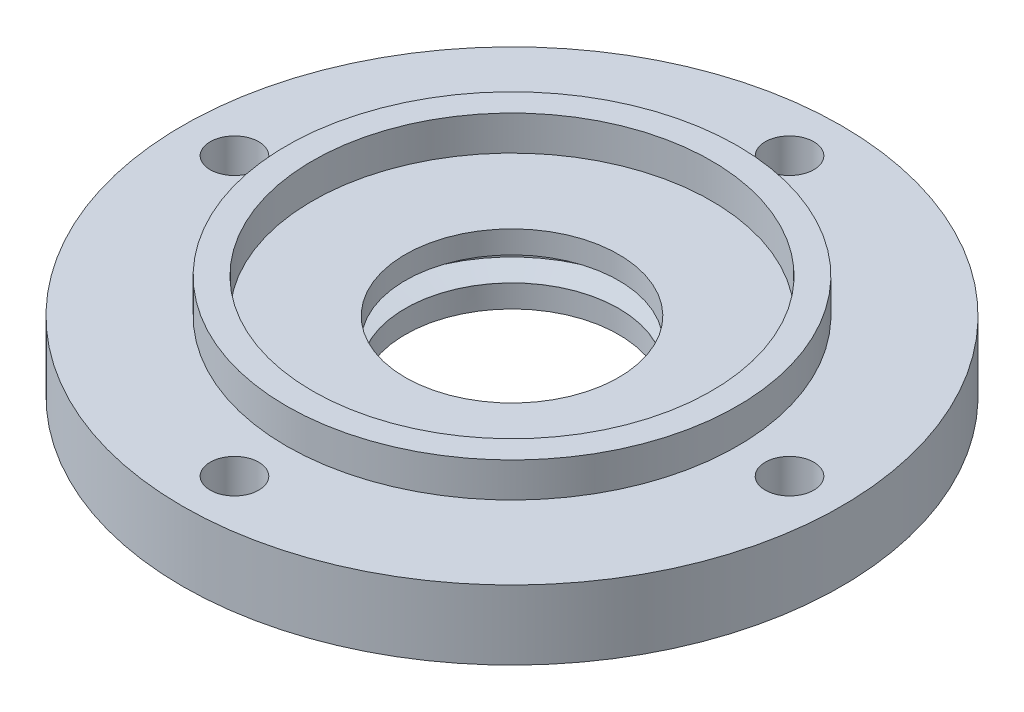
SolidWorks part; units mm, degrees
ref_plane "Front Plane" through (0, 0, 0) normal (0, 0, 1) x (1, 0, 0)
ref_plane "Top Plane" through (0, 0, 0) normal (0, 1, 0) x (1, 0, 0)
ref_plane "Right Plane" through (0, 0, 0) normal (1, 0, 0) x (0, 0, -1)
sketch "Sketch1" plane through (0, 0, 0) normal (0, 1, 0) x (1, 0, 0)
  circle A0 centre (0, 0) radius 95
  dimension "D1" = 190
extrude "Boss-Extrude1" add sketch "Sketch1" along normal mid plane 20 contours A0
sketch "Sketch2" plane through (0, 10, 0) normal (0, 1, 0) x (1, 0, 0)
  circle A0 centre (0, 0) radius 65
  dimension "D1" = 130
extrude "Boss-Extrude2" add sketch "Sketch2" along normal blind 10
sketch "Sketch3" plane through (0, 20, 0) normal (0, 1, 0) x (1, 0, 0)
  circle A0 centre (0, 0) radius 57.5
  dimension "D1" = 115
extrude "Cut-Extrude1" cut sketch "Sketch3" against normal blind 10
sketch "Sketch4" plane through (0, 10, 0) normal (0, 1, 0) x (1, 0, 0)
  line L0 (0, -105.345) -> (0, 103.136) construction
  circle A0 centre (0, 80) radius 7
  circle A1 centre (80, 0) radius 7
  circle A2 centre (0, -80) radius 7
  circle A3 centre (-80, 0) radius 7
  point P15 (0, 0)
  dimension "D2" = 14
  dimension "D1" = 80
  dimension "D3" = 4
extrude "Cut-Extrude2" cut sketch "Sketch4" against normal through all
sketch "Sketch5" plane through (0, 10, 0) normal (0, 1, 0) x (1, 0, 0)
  circle A0 centre (0, 0) radius 30.75
  dimension "D1" = 61.5
extrude "Cut-Extrude3" cut sketch "Sketch5" against normal through all
sketch "Sketch6" plane through (0, 0, 0) normal (1, 0, 0) x (0, 0, -1)
  line L0 (0, -20.8168) -> (0, 0) construction
  line L13 (0, 3.5) -> (-30.8148, 3.5)
  line L14 (-38.5, -2.5) -> (-38.5, 2.5)
  line L15 (-30.8148, 3.5) -> (-38.5, 2.5)
  line L18 (0, 3.5) -> (0, -3.5)
  line L19 (0, -3.5) -> (-30.8148, -3.5)
  line L21 (-30.8148, -3.5) -> (-38.5, -2.5)
  line L22 (0, 2.5) -> (0, 32.2846) construction
  point P2 (0, 0)
  dimension "D3" = 3.5
  dimension "D4" = 3.5
  dimension "D7" = 7.75
  dimension "D8" = 7.75
revolve "Cut-Revolve3" cut sketch "Sketch6" angle 360 about L18
